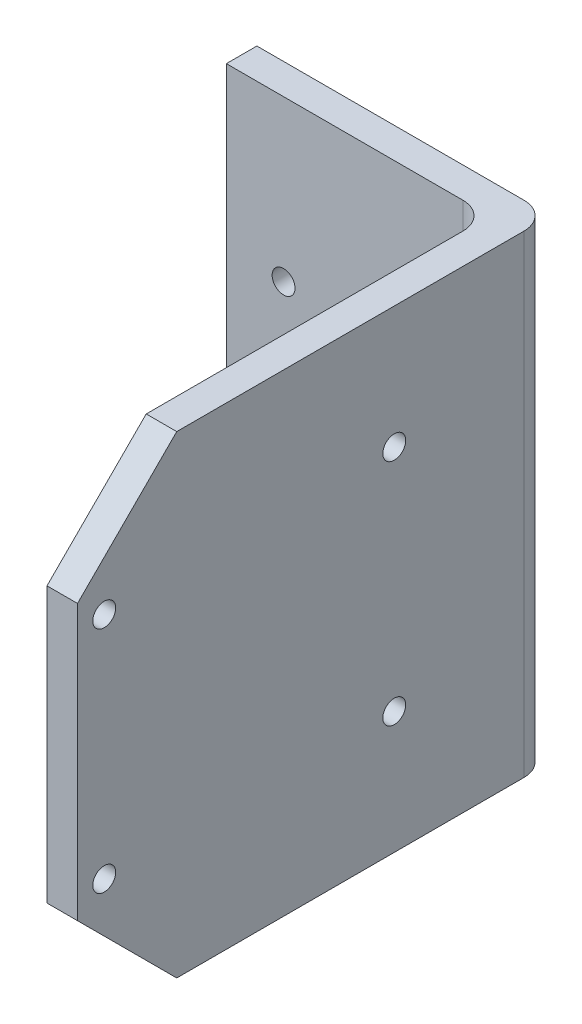
SolidWorks part; units mm, degrees
ref_plane "前视基准面" through (0, 0, 0) normal (0, 0, 1) x (1, 0, 0)
ref_plane "上视基准面" through (0, 0, 0) normal (0, 1, 0) x (1, 0, 0)
ref_plane "右视基准面" through (0, 0, 0) normal (1, 0, 0) x (0, 0, -1)
other "Configuration Table"
sketch "草图1" plane through (0, 0, 0) normal (0, 1, 0) x (1, 0, 0)
  line L0 (-27.626, 43.1575) -> (10.874, 43.1575)
  line L1 (10.874, 43.1575) -> (10.874, -18.8425)
  line L2 (10.874, -18.8425) -> (6.874, -18.8425)
  line L3 (6.874, -18.8425) -> (6.874, 39.1575)
  line L4 (6.874, 39.1575) -> (-27.626, 39.1575)
  line L5 (-27.626, 39.1575) -> (-27.626, 43.1575)
  dimension "D1" = 38.5
  dimension "D2" = 62
  dimension "D3" = 4
  dimension "D4" = 4
extrude "凸台-拉伸1" add sketch "草图1" along normal mid plane 62
ref_plane "基准面1" through (10.874, 0, 0) normal (1, 0, 0) x (0, 0, -1)
sketch "草图2" plane through (10.874, 0, 0) normal (1, 0, 0) x (0, 0, -1)
  line L0 (-18.8425, 31) -> (-18.8425, -31) construction
  line L1 (-18.8425, -31) -> (43.1575, -31) construction
  line L2 (43.1575, 31) -> (43.1575, -31) construction
  line L3 (-18.8425, 31) -> (43.1575, 31) construction
  line L4 (-18.8425, 31) -> (-18.8425, -31)
  line L5 (-18.8425, -31) -> (43.1575, -31)
  line L6 (43.1575, 31) -> (43.1575, -31)
  line L7 (-18.8425, 31) -> (43.1575, 31)
  line L8 (43.1575, 0) -> (-18.8425, 0)
  line L9 (22.6575, 0) -> (22.6575, -15)
  line L12 (-18.8425, -18) -> (-5.8425, -31)
  line L13 (-18.8425, 18) -> (-5.8425, 31)
  circle A0 centre (22.6575, -15) radius 1.5
  circle A1 centre (22.6575, 15) radius 1.5
  circle A2 centre (-15.3425, 15) radius 1.5
  circle A3 centre (-15.3425, -15) radius 1.5
  dimension "D2" = 18
  dimension "D1" = 41.5
  dimension "D3" = 30
extrude "切除-拉伸2" cut sketch "草图2" against normal blind 10
ref_plane "基准面2" through (0, 0, -43.1575) normal (0, 0, -1) x (-1, 0, 0)
fillet "圆角1" radius 3.5 1 edges at (10.874, 0, -43.1575)
fillet "圆角2" radius 3.5 1 edges at (6.874, 0, -39.1575)
sketch "草图7" plane through (0, 0, -43.1575) normal (0, 0, -1) x (-1, 0, 0)
  line L0 (27.626, 31) -> (27.626, -31) construction
  line L1 (-7.374, 31) -> (27.626, 31) construction
  line L2 (27.626, 31) -> (27.626, -31)
  line L3 (-7.374, 31) -> (27.626, 31)
  line L6 (27.626, 0) -> (20.126, 0)
  line L7 (20.126, 0) -> (2.0345, 0)
  circle A0 centre (20.126, 10) radius 1.5
  circle A1 centre (20.126, -10) radius 1.5
  point P3 (0, 0)
  dimension "D2" = 10
  dimension "D3" = 10
extrude "切除-拉伸4" cut sketch "草图7" against normal blind 10 contours A0 | A1
